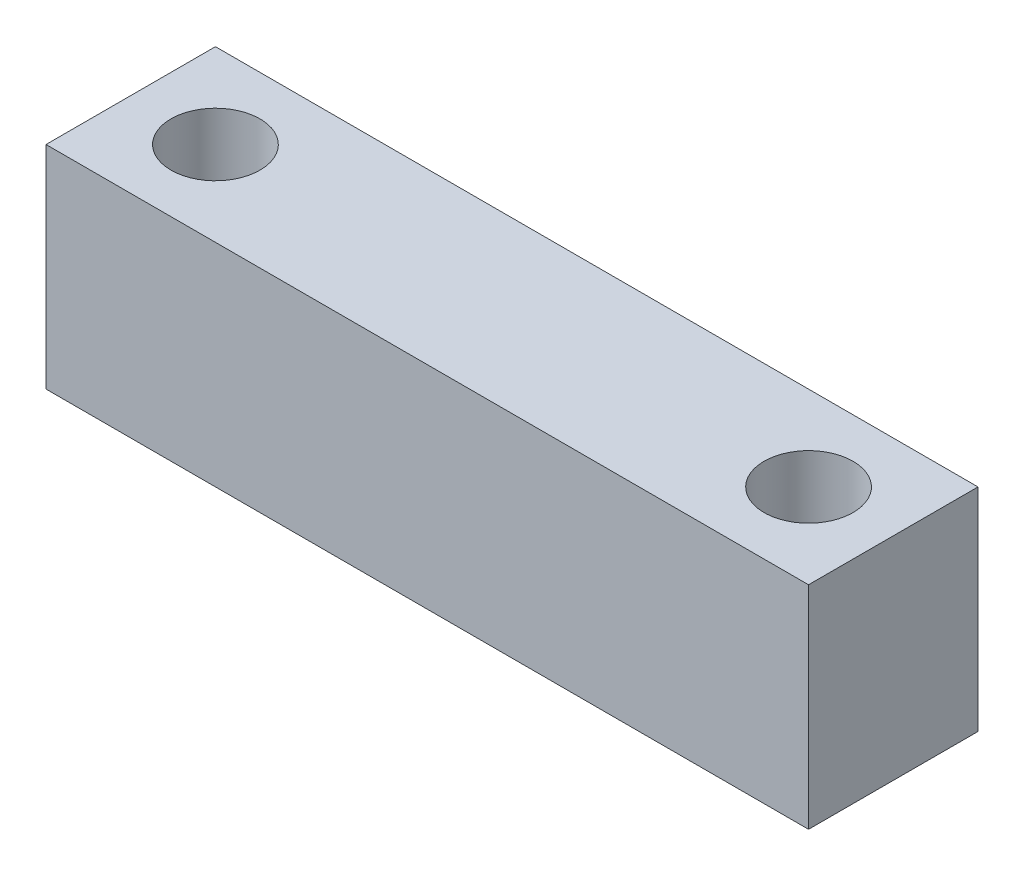
SolidWorks part; units mm, degrees
material "Balsa"
ref_plane "Front Plane" through (0, 0, 0) normal (0, 0, 1) x (1, 0, 0)
ref_plane "Top Plane" through (0, 0, 0) normal (0, 1, 0) x (1, 0, 0)
ref_plane "Right Plane" through (0, 0, 0) normal (1, 0, 0) x (0, 0, -1)
sketch "Sketch1" plane through (0, 0, 0) normal (0, 1, 0) x (1, 0, 0)
  line L1 (0, 0) -> (36, 0)
  line L2 (0, 0) -> (0, -8)
  line L3 (0, -8) -> (36, -8)
  line L4 (36, 0) -> (36, -8)
  line L5 (18, 0) -> (18, -8) construction
  line L6 (0, -4) -> (36, -4) construction
  circle A0 centre (4, -4) radius 2.1
  circle A1 centre (32, -4) radius 2.1
  dimension "D2" = 4.2
  dimension "D1" = 36
  dimension "D3" = 4
  dimension "D4" = 28
  dimension "D5" = 4
extrude "Boss-Extrude1" add sketch "Sketch1" along normal blind 10
